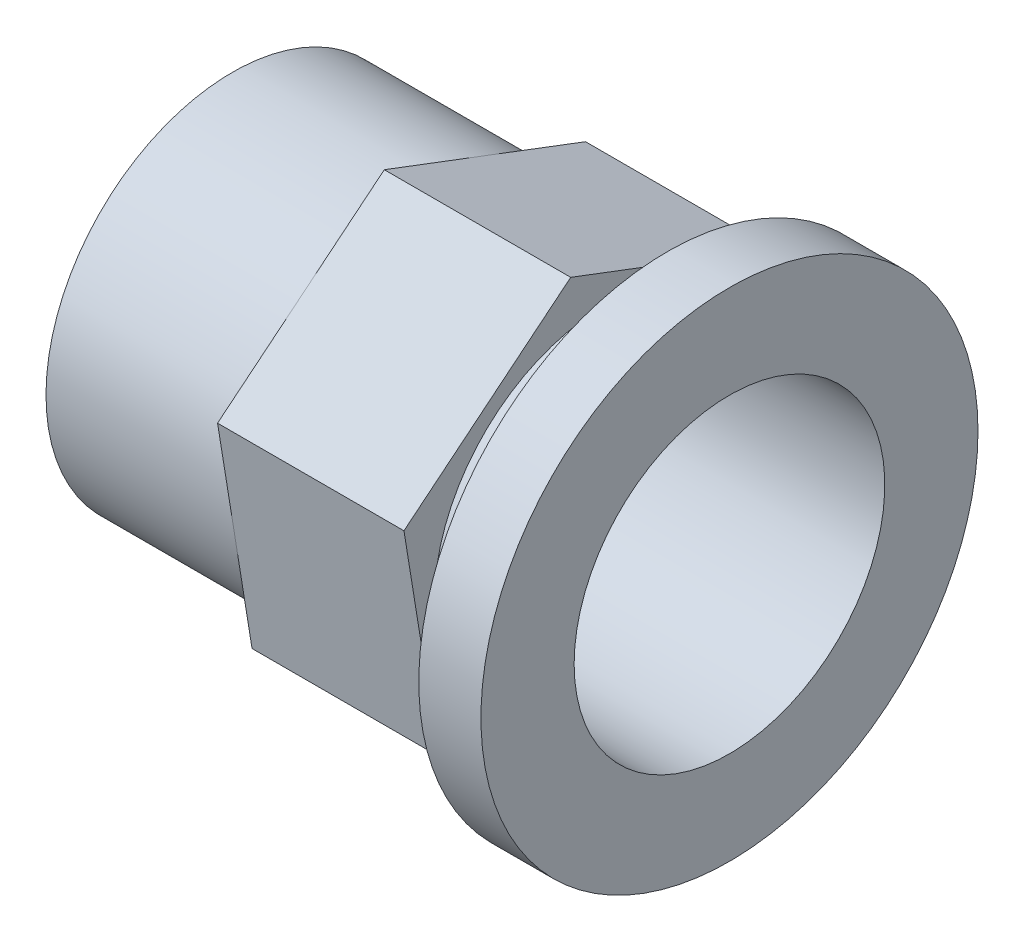
SolidWorks part; units mm, degrees
ref_plane "前视基准面" through (0, 0, 0) normal (0, 0, 1) x (1, 0, 0)
ref_plane "上视基准面" through (0, 0, 0) normal (0, 1, 0) x (1, 0, 0)
ref_plane "右视基准面" through (0, 0, 0) normal (1, 0, 0) x (0, 0, -1)
sketch "草图1" plane through (0, 0, 0) normal (1, 0, 0) x (0, 0, -1)
  circle A0 centre (0, 0) radius 3
  dimension "D1" = 6
extrude "凸台-拉伸1" add sketch "草图1" along normal blind 3
sketch "草图2" plane through (3, 0, 0) normal (1, 0, 0) x (0, 0, -1)
  line L1 (3.2388, -1.2288) -> (2.6836, 2.1905)
  line L2 (2.6836, 2.1905) -> (-0.5553, 3.4193)
  line L3 (-0.5553, 3.4193) -> (-3.2388, 1.2288)
  line L4 (-3.2388, 1.2288) -> (-2.6836, -2.1905)
  line L5 (-2.6836, -2.1905) -> (0.5553, -3.4193)
  line L6 (0.5553, -3.4193) -> (3.2388, -1.2288)
  circle A0 centre (0, 0) radius 3 construction
  dimension "D1" = 6
extrude "凸台-拉伸2" add sketch "草图2" along normal blind 3
sketch "草图3" plane through (6, 0, 0) normal (1, 0, 0) x (0, 0, -1)
  circle A0 centre (0, 0) radius 2.75
  dimension "D1" = 5.5
extrude "凸台-拉伸3" add sketch "草图3" along normal blind 1
sketch "草图4" plane through (7, 0, 0) normal (1, 0, 0) x (0, 0, -1)
  circle A0 centre (0, 0) radius 4
  dimension "D1" = 8
extrude "凸台-拉伸4" add sketch "草图4" along normal blind 1
sketch "草图5" plane through (0, 0, 0) normal (-1, 0, 0) x (0, 0, 1)
  circle A0 centre (0, 0) radius 2.5
  dimension "D1" = 5
extrude "切除-拉伸1" cut sketch "草图5" against normal through all
